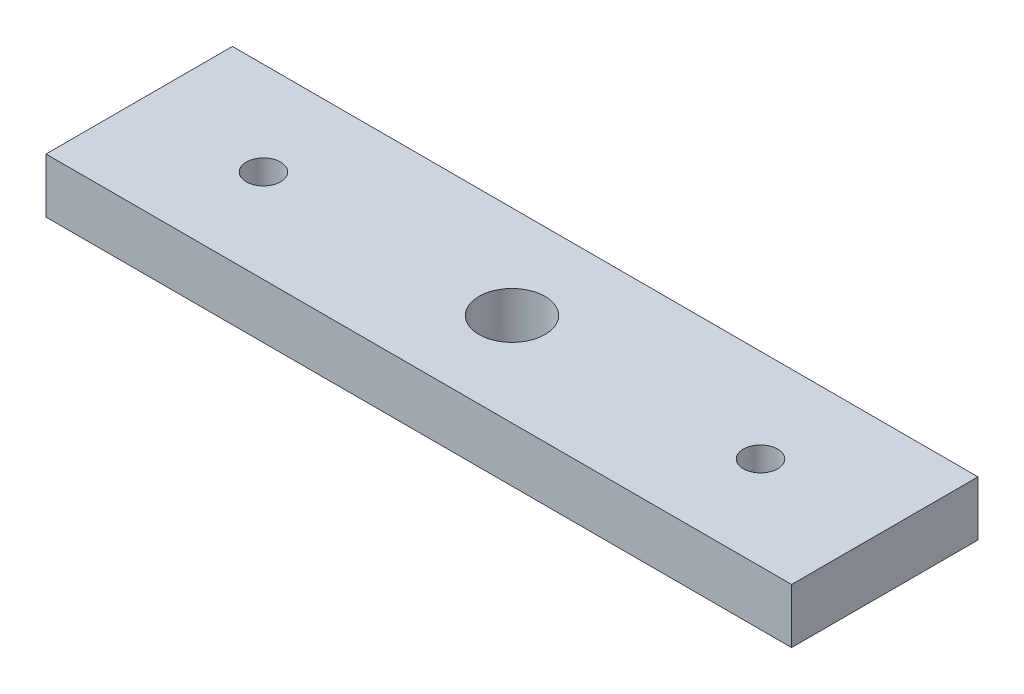
SolidWorks part; units mm, degrees
material "Beech"
ref_plane "Front Plane" through (0, 0, 0) normal (0, 0, 1) x (1, 0, 0)
ref_plane "Top Plane" through (0, 0, 0) normal (0, 1, 0) x (1, 0, 0)
ref_plane "Right Plane" through (0, 0, 0) normal (1, 0, 0) x (0, 0, -1)
sketch "Sketch1" plane through (0, 0, 0) normal (0, 1, 0) x (1, 0, 0)
  line L1 (-38.1, -9.525) -> (38.1, -9.525)
  line L2 (-38.1, -9.525) -> (-38.1, 9.525)
  line L3 (-38.1, 9.525) -> (38.1, 9.525)
  line L4 (38.1, -9.525) -> (38.1, 9.525)
  line L5 (-38.1, -9.525) -> (38.1, 9.525) construction
  line L6 (-38.1, 9.525) -> (38.1, -9.525) construction
  point P0 (0, 0)
  dimension "D1" = 76.2
  dimension "D2" = 19.05
extrude "Boss-Extrude1" add sketch "Sketch1" along normal blind 5.588
hole_wizard "1/4 Clearance Hole1" positions "Sketch3" profile "Sketch2" hole size "1/4" standard "ANSI Inch"
sketch "Sketch3" plane through (0, 5.588, 0) normal (0, 1, 0) x (1, 0, 0)
  point P0 (0, 0)
sketch "Sketch2" plane through (0, 5.588, 0) normal (1, 0, 0) x (0, 0, 1)
  line L0 (0, 0) -> (0, 21.0798)
  line L1 (0, 21.0798) -> (3.3782, 19.05)
  line L2 (3.3782, 19.05) -> (3.3782, 0)
  line L5 (3.3782, 0) -> (0, 0)
  line L10 (0, 21.0798) -> (-3.3782, 19.05) construction
  line L11 (0, -6.35) -> (0, 107.95) construction
  dimension "Hole Dia." = 6.7564
  dimension "Hole Depth" = 19.05
  dimension "Drill Angle" = 118
hole_wizard "#6 Clearance Hole1" positions "Sketch4" profile "Sketch5" hole size "#6" standard "ANSI Inch" end condition up to next
sketch "Sketch4" plane through (0, 5.588, 0) normal (0, 1, 0) x (1, 0, 0)
  line L0 (-25.4, 0) -> (25.4, 0) construction
  point P0 (25.4, 0)
  point P2 (-25.4, 0)
  dimension "D1" = 50.8
sketch "Sketch5" plane through (25.4, 5.588, 0) normal (1, 0, 0) x (0, 0, 1)
  line L0 (0, 0) -> (0, 5.588)
  line L1 (0, 5.588) -> (1.7526, 5.588)
  line L2 (1.7526, 5.588) -> (1.7526, 0)
  line L5 (1.7526, 0) -> (0, 0)
  line L11 (0, -6.35) -> (0, 107.95) construction
  dimension "Thru Hole Dia." = 3.5052
  dimension "Thru Hole Depth" = 5.588
